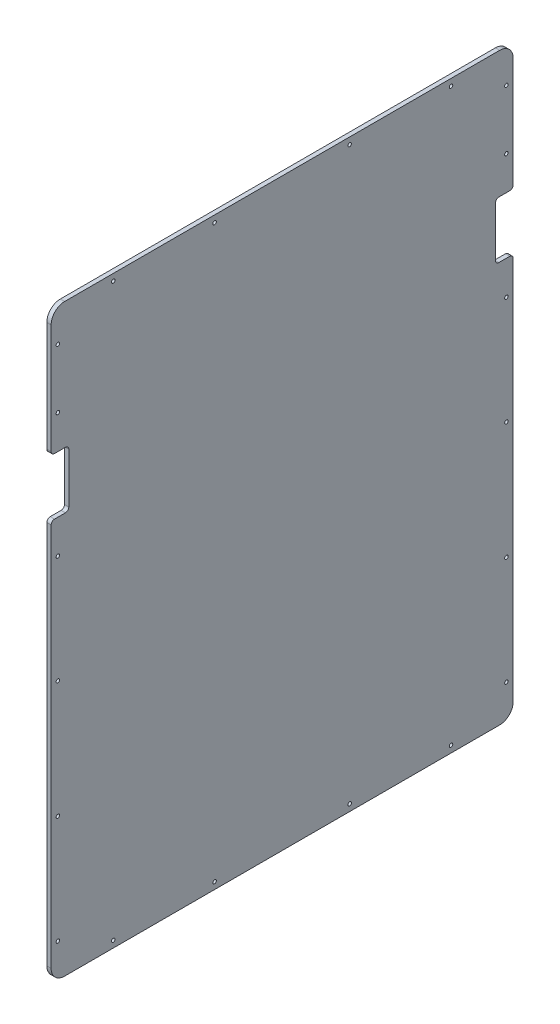
SolidWorks part; units mm, degrees
other "Markup1"
sketch "Sketch6"
sketch "Sketch7"
material "Acrylic (Medium-high impact)"
ref_plane "Front Plane" through (0, 0, 0) normal (0, 0, 1) x (1, 0, 0)
ref_plane "Top Plane" through (0, 0, 0) normal (0, 1, 0) x (1, 0, 0)
ref_plane "Right Plane" through (0, 0, 0) normal (1, 0, 0) x (0, 0, -1)
sketch "Sketch1" plane through (0, 0, 0) normal (1, 0, 0) x (0, 0, -1)
  line L1 (-342, 432.5) -> (342, 432.5)
  line L2 (-342, 432.5) -> (-342, -432.5)
  line L3 (-342, -432.5) -> (342, -432.5)
  line L4 (342, 432.5) -> (342, -432.5)
  line L5 (-342, 432.5) -> (342, -432.5) construction
  line L6 (-342, -432.5) -> (342, 432.5) construction
  point P0 (0, 0)
  dimension "D1" = 865
  dimension "D2" = 684
extrude "Boss-Extrude1" add sketch "Sketch1" along normal blind 6.35
fillet "Fillet1" radius 20 4 edges at (3.175, -432.5, 342) (3.175, -432.5, -342) (3.175, 432.5, -342) (3.175, 432.5, 342)
sketch "Sketch3" plane through (6.35, 0, 0) normal (1, 0, 0) x (0, 0, -1)
  line L0 (-342, 412.5) -> (-342, -412.5) construction
  line L1 (-342, 245) -> (-315.85, 245)
  line L2 (-342, 245) -> (-342, 161)
  line L3 (-342, 161) -> (-315.85, 161)
  line L4 (-315.85, 245) -> (-315.85, 161)
  line L5 (322, 432.5) -> (-322, 432.5) construction
  dimension "D1" = 187.5
  dimension "D2" = 84
  dimension "D3" = 26.15
extrude "Cut-Extrude2" cut sketch "Sketch3" against normal through all contours L1 L4 L3 L2
mirror "Mirror1" about plane through (0, 0, 0) normal (0, 0, 1) of "Cut-Extrude2"
fillet "Fillet2" radius 5 8 edges at (3.175, 245, 315.85) (3.175, 161, 315.85) (3.175, 161, 342) (3.175, 245, 342) (3.175, 161, -315.85) (3.175, 161, -342) (3.175, 245, -315.85) (3.175, 245, -342)
sketch "Sketch4" plane through (0, 0, 0) normal (-1, 0, 0) x (0, 0, 1)
  line L12 (-322, 432.5) -> (322, 432.5) construction
  line L13 (-337, 245) -> (-320.85, 245) construction
  line L14 (-337, 161) -> (-320.85, 161) construction
  line L15 (322, -432.5) -> (-322, -432.5) construction
  line L16 (0, 0) -> (137.732, 0) construction
  line L17 (0, 0) -> (0, 157.3363) construction
  line L24 (-320.85, 151) -> (-332, 151)
  line L25 (-332, 151) -> (-332, -412.5)
  line L26 (-322, -422.5) -> (322, -422.5)
  line L27 (332, -412.5) -> (332, 151)
  line L28 (332, 151) -> (320.85, 151)
  line L29 (305.85, 166) -> (305.85, 240)
  line L30 (320.85, 255) -> (332, 255)
  line L31 (332, 255) -> (332, 412.5)
  line L32 (322, 422.5) -> (-322, 422.5)
  line L33 (-332, 412.5) -> (-332, 255)
  line L34 (-332, 255) -> (-320.85, 255)
  line L35 (-305.85, 240) -> (-305.85, 166)
  line L36 (-320.85, 151) -> (-332, 151)
  line L37 (-332, 151) -> (-332, -412.5)
  line L38 (-322, -422.5) -> (322, -422.5)
  line L39 (332, -412.5) -> (332, 151)
  line L40 (332, 151) -> (320.85, 151)
  line L41 (305.85, 166) -> (305.85, 240)
  line L42 (320.85, 255) -> (332, 255)
  line L43 (332, 255) -> (332, 412.5)
  line L44 (322, 422.5) -> (-322, 422.5)
  line L45 (-332, 412.5) -> (-332, 255)
  line L46 (-332, 255) -> (-320.85, 255)
  line L47 (-305.85, 240) -> (-305.85, 166)
  circle A12 centre (-250, 422.5) radius 2.6
  circle A13 centre (250, 422.5) radius 2.6
  circle A14 centre (-100, 422.5) radius 2.6
  circle A15 centre (100, 422.5) radius 2.6
  circle A16 centre (-332, 382.5) radius 2.6
  circle A17 centre (-332, 295) radius 2.6
  circle A18 centre (-332, 111) radius 2.6
  circle A19 centre (-332, -49) radius 2.6
  circle A20 centre (-332, -382.5) radius 2.6
  circle A21 centre (-332, -222.5) radius 2.6
  circle A22 centre (250, -422.5) radius 2.6
  circle A23 centre (100, -422.5) radius 2.6
  arc A24 (-332, -412.5) -> (-322, -422.5) centre (-322, -412.5) ccw
  arc A25 (322, -422.5) -> (332, -412.5) centre (322, -412.5) ccw
  arc A26 (305.85, 166) -> (320.85, 151) centre (320.85, 166) ccw
  arc A27 (320.85, 255) -> (305.85, 240) centre (320.85, 240) ccw
  arc A28 (332, 412.5) -> (322, 422.5) centre (322, 412.5) ccw
  arc A29 (-322, 422.5) -> (-332, 412.5) centre (-322, 412.5) ccw
  arc A30 (-305.85, 240) -> (-320.85, 255) centre (-320.85, 240) ccw
  arc A31 (-320.85, 151) -> (-305.85, 166) centre (-320.85, 166) ccw
  arc A32 (-332, -412.5) -> (-322, -422.5) centre (-322, -412.5) ccw
  arc A33 (322, -422.5) -> (332, -412.5) centre (322, -412.5) ccw
  arc A34 (305.85, 166) -> (320.85, 151) centre (320.85, 166) ccw
  arc A35 (320.85, 255) -> (305.85, 240) centre (320.85, 240) ccw
  arc A36 (332, 412.5) -> (322, 422.5) centre (322, 412.5) ccw
  arc A37 (-322, 422.5) -> (-332, 412.5) centre (-322, 412.5) ccw
  arc A38 (-305.85, 240) -> (-320.85, 255) centre (-320.85, 240) ccw
  arc A39 (-320.85, 151) -> (-305.85, 166) centre (-320.85, 166) ccw
  circle A40 centre (-100, -422.5) radius 2.6
  circle A41 centre (-250, -422.5) radius 2.6
  circle A42 centre (332, 382.5) radius 2.6
  circle A43 centre (332, 295) radius 2.6
  circle A44 centre (332, 111) radius 2.6
  circle A45 centre (332, -49) radius 2.6
  circle A46 centre (332, -222.5) radius 2.6
  circle A47 centre (332, -382.5) radius 2.6
  dimension "D6" = 5.2
  dimension "D7" = 5.2
  dimension "D8" = 5.2
  dimension "D9" = 5.2
  dimension "D11" = 50
  dimension "D16" = 5.2
  dimension "D17" = 5.2
  dimension "D18" = 5.2
  dimension "D19" = 5.2
  dimension "D20" = 5.2
  dimension "D21" = 5.2
  dimension "D2" = 100
  dimension "D3" = 250
  dimension "D4" = 100
  dimension "D5" = 250
  dimension "D10" = 50
  dimension "D12" = 50
  dimension "D13" = 50
  dimension "D14" = 160
  dimension "D15" = 160
  dimension "D1" = 10
extrude "Cut-Extrude3" cut sketch "Sketch4" against normal through all contours L44 A14 | L44 A14 | L44 A15 | L44 A15 | L44 A13 | L44 A13 | A42 L43 | A42 L43 | A46 L39 | A46 L39 | A41 L38 | A41 L38 | L37 A20 | L37 A20 | L37 A21 | L37 A21 | L37 A19 | L37 A19 | L37 A18 | L37 A18 | L45 A17 | L45 A17 | L45 A16 | L45 A16 | A12 | A43 | A44 | A45 | A47 | A22 | A23 | A40
sketch "Sketch2" plane through (6.35, 0, 0) normal (1, 0, 0) x (0, 0, -1)
  line L0 (-67, 182.5) -> (67, 42.5) construction
  line L1 (-67, 182.5) -> (67, 182.5) construction
  line L2 (-67, 182.5) -> (-67, 42.5) construction
  line L3 (-67, 42.5) -> (67, 42.5) construction
  line L4 (67, 182.5) -> (67, 42.5) construction
  line L5 (-67, 42.5) -> (67, 182.5) construction
  line L6 (-342, 412.5) -> (-342, 432.5) construction
  line L7 (-342, 432.5) -> (-322, 432.5) construction
  line L8 (322, 432.5) -> (342, 432.5) construction
  line L9 (322, 432.5) -> (-322, 432.5) construction
  line L10 (342, 432.5) -> (342, 412.5) construction
  circle A0 centre (-62, 177.5) radius 1.65
  circle A1 centre (62, 177.5) radius 1.65
  circle A2 centre (62, 47.5) radius 1.65
  circle A3 centre (-62, 47.5) radius 1.65
  arc A4 (342, 412.5) -> (322, 432.5) centre (322, 412.5) ccw construction
  point P4 (0, 112.5)
  dimension "D3" = 3.3
  dimension "D6" = 5
  dimension "D7" = 135
  dimension "D8" = 129
  dimension "D9" = 5
  dimension "D10" = 129
  dimension "D1" = 140
  dimension "D2" = 134
  dimension "D4" = 5
  dimension "D5" = 5
  dimension "D11" = 275
  dimension "D12" = 250
extrude "Cut-Extrude1" [suppressed] cut sketch "Sketch2" against normal through all
sketch "Sketch5" plane through (6.35, 0, 0) normal (1, 0, 0) x (0, 0, -1)
  line L0 (-192, -117.5) -> (-192, -357.5) construction
  line L1 (-190, -117.5) -> (-190, -357.5)
  line L2 (-194, -117.5) -> (-194, -357.5)
  line L3 (-81, -121.5) -> (-81, -353.5) construction
  line L4 (-79, -121.5) -> (-79, -353.5)
  line L5 (-83, -121.5) -> (-83, -353.5)
  line L6 (-322, 432.5) -> (-342, 432.5) construction
  line L7 (-342, 432.5) -> (-342, 412.5) construction
  arc A0 (-190, -117.5) -> (-194, -117.5) centre (-192, -117.5) ccw
  arc A1 (-194, -357.5) -> (-190, -357.5) centre (-192, -357.5) ccw
  arc A2 (-79, -121.5) -> (-83, -121.5) centre (-81, -121.5) ccw
  arc A3 (-83, -353.5) -> (-79, -353.5) centre (-81, -353.5) ccw
  point P2 (-192, -237.5)
  point P8 (-81, -237.5)
  dimension "D4" = 2
  dimension "D5" = 2
  dimension "D1" = 111
  dimension "D2" = 240
  dimension "D3" = 232
  dimension "D6" = 150
  dimension "D7" = 550
extrude "Cut-Extrude4" [suppressed] cut sketch "Sketch5" against normal blind 10
